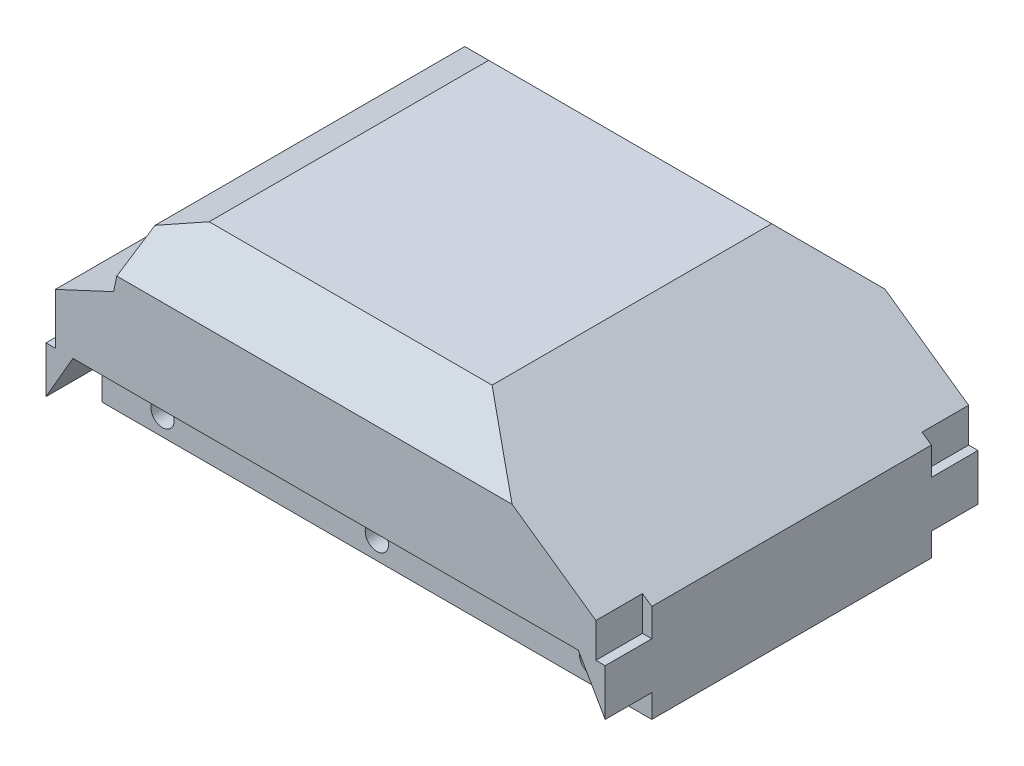
SolidWorks part; units mm, degrees
ref_plane "Front Plane" through (0, 0, 0) normal (0, 0, 1) x (1, 0, 0)
ref_plane "Top Plane" through (0, 0, 0) normal (0, 1, 0) x (1, 0, 0)
ref_plane "Right Plane" through (0, 0, 0) normal (1, 0, 0) x (0, 0, -1)
sketch "Sketch1" plane through (44.2247, 74.8917, 130.2829) normal (0, 1, 0) x (1, 0, 0)
  line L0 (-73.66, -50.8) -> (-73.66, -19.05)
  line L1 (-73.66, -19.05) -> (-76.2, -19.05)
  line L2 (-76.2, -19.05) -> (-76.2, 19.05)
  line L3 (-76.2, 19.05) -> (-73.66, 19.05)
  line L4 (-73.66, 19.05) -> (-73.66, 50.8)
  line L5 (-73.66, 50.8) -> (73.66, 50.8)
  line L6 (73.66, 50.8) -> (73.66, 38.1)
  line L7 (73.66, 38.1) -> (76.2, 38.1)
  line L8 (76.2, 38.1) -> (76.2, -38.1)
  line L9 (76.2, -38.1) -> (73.66, -38.1)
  line L10 (73.66, -38.1) -> (73.66, -50.8)
  line L11 (73.66, -50.8) -> (-73.66, -50.8)
extrude "Boss-Extrude1" add sketch "Sketch1" along normal blind 38.1
sketch "Sketch2" plane through (44.2247, 74.8917, 130.2829) normal (0, 0, 1) x (1, 0, 0)
  line L0 (-76.2, 12.7) -> (-57.7838, 21.2876)
  line L1 (-76.2, 38.1) -> (-76.2, 0) construction
  line L2 (-57.7838, 21.2876) -> (-55.0844, 33.9876)
  line L3 (-55.0844, 33.9876) -> (-44.45, 38.1)
  line L4 (-73.66, 38.1) -> (73.66, 38.1) construction
  line L5 (-44.45, 38.1) -> (-76.2, 38.1)
  line L6 (-76.2, 38.1) -> (-76.2, 12.7)
  line L7 (32.67, 38.1) -> (76.2, 7.62)
  line L8 (76.2, 38.1) -> (76.2, 0) construction
  line L9 (76.2, 7.62) -> (76.2, 38.1)
  line L10 (76.2, 38.1) -> (32.67, 38.1)
  line L11 (-73.66, 0) -> (73.66, 0) construction
  point P20 (-74.513, -4.8412)
  dimension "D1" = 25
  dimension "D2" = 20.32
  dimension "D3" = 25.4
  dimension "D4" = 31.75
  dimension "D5" = 12.7
  dimension "D6" = 12
  dimension "D7" = 35
  dimension "D8" = 30.48
extrude "Cut-Extrude1" cut sketch "Sketch2" against normal through all and the other way through all
sketch "Sketch3" plane through (44.2247, 74.8917, 130.2829) normal (0, 0, 1) x (1, 0, 0)
  line L0 (-76.2, 0) -> (-76.2, -12.7)
  line L1 (-76.2, -12.7) -> (-68.8677, 0)
  line L2 (-73.66, 0) -> (73.66, 0) construction
  line L3 (-68.8677, 0) -> (-76.2, 0)
  line L4 (76.2, 0) -> (76.2, -12.7)
  line L5 (76.2, -12.7) -> (68.8677, 0)
  line L6 (-73.66, 0) -> (73.66, 0) construction
  line L7 (68.8677, 0) -> (76.2, 0)
  dimension "D1" = 12.7
  dimension "D2" = 30
  dimension "D3" = 30
extrude "Boss-Extrude2" add sketch "Sketch3" along normal up to surface and the other way up to surface up to face at (28.6437, 94.2364, 181.0829) other way up to face at (28.6437, 94.2364, 79.4829)
sketch "Sketch4" plane through (44.2247, 74.8917, 130.2829) normal (1, 0, 0) x (0, 0, -1)
  line L0 (-38.1, 38.1) -> (-50.8, 25.4)
  line L1 (50.8, 38.1) -> (-50.8, 38.1) construction
  line L2 (-50.8, 38.1) -> (-50.8, 9.3985) construction
  line L3 (-50.8, 25.4) -> (-50.8, 38.1)
  line L4 (-50.8, 38.1) -> (-38.1, 38.1)
  line L5 (0, 38.1) -> (0, -12.7) construction
  line L6 (-50.8, -12.7) -> (50.8, -12.7) construction
  line L7 (38.1, 38.1) -> (50.8, 25.4)
  line L8 (50.8, 38.1) -> (38.1, 38.1)
  line L9 (50.8, 25.4) -> (50.8, 38.1)
  dimension "D1" = 12.7
  dimension "D2" = 45
extrude "Cut-Extrude2" cut sketch "Sketch4" against normal through all and the other way through all
sketch "Sketch5" plane through (0, 74.8917, 0) normal (0, -1, 0) x (1, 0, 0)
  line L1 (-29.4353, 168.3829) -> (120.4247, 168.3829)
  line L2 (-29.4353, 168.3829) -> (-29.4353, 92.1829)
  line L3 (-29.4353, 92.1829) -> (120.4247, 92.1829)
  line L4 (120.4247, 168.3829) -> (120.4247, 92.1829)
extrude "Boss-Extrude4" add sketch "Sketch5" along normal blind 19.05
sketch "Sketch6" plane through (0, 0, 92.1829) normal (0, 0, -1) x (-1, 0, 0)
  line L0 (29.4353, 61.2164) -> (-120.4247, 61.2164) construction
  line L1 (29.4353, 55.8417) -> (29.4353, 66.5911) construction
  line L2 (-120.4247, 55.8417) -> (-120.4247, 62.1917) construction
  circle A0 centre (-103.9147, 61.2164) radius 3.175
  circle A1 centre (-45.4947, 61.2164) radius 3.175
  circle A2 centre (12.9253, 61.2164) radius 3.175
  point P12 (0, 0)
  point P14 (-8.727, 62.8138)
  dimension "D3" = 6.35
  dimension "D1" = 58.42
  dimension "D2" = 58.42
extrude "Cut-Extrude3" cut sketch "Sketch6" against normal through all
